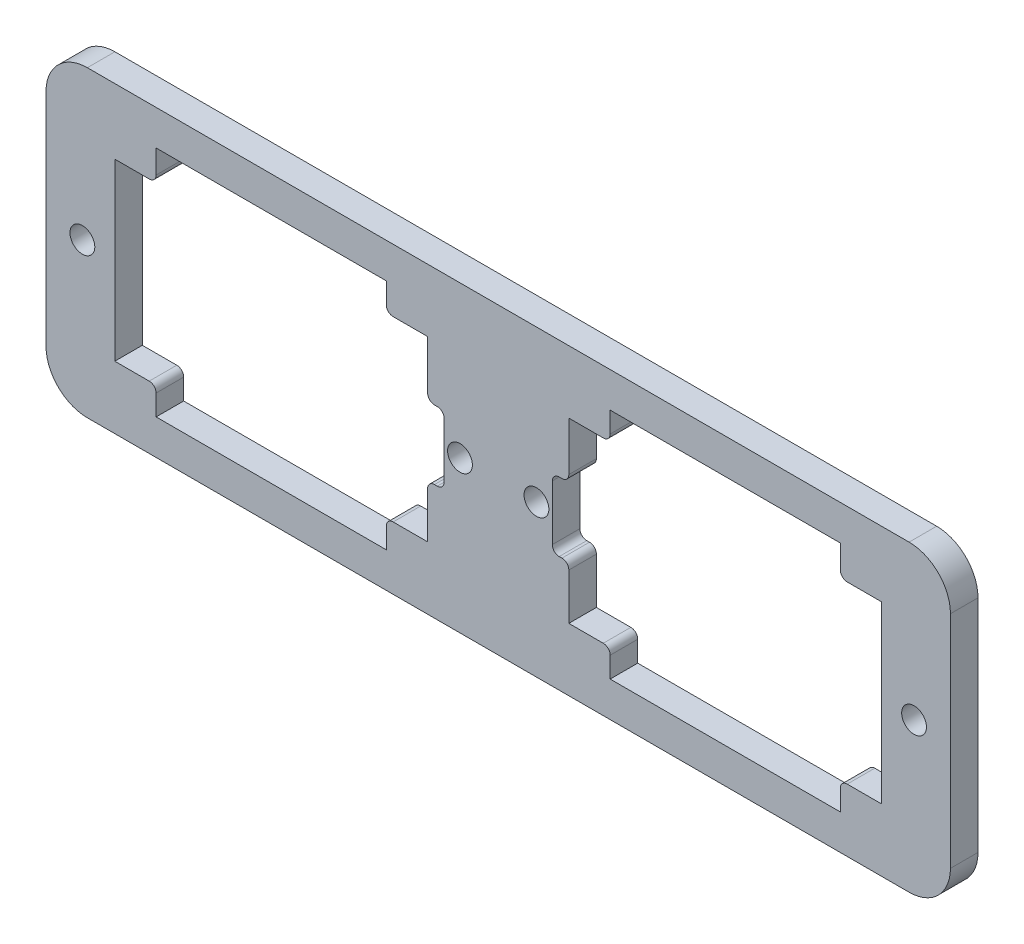
SolidWorks part; units mm, degrees
ref_plane "前视基准面" through (0, 0, 0) normal (0, 0, 1) x (1, 0, 0)
ref_plane "上视基准面" through (0, 0, 0) normal (0, 1, 0) x (1, 0, 0)
ref_plane "右视基准面" through (0, 0, 0) normal (1, 0, 0) x (0, 0, -1)
sketch "草图1" plane through (0, 0, 0) normal (0, 0, 1) x (1, 0, 0)
  line L0 (-29.8125, 11) -> (29.8125, 11)
  line L1 (32.8125, 8) -> (32.8125, -8)
  line L2 (29.8125, -11) -> (-29.8125, -11)
  line L3 (4.623, 2.4) -> (4.423, 2.4)
  line L4 (5.123, 6.45) -> (5.123, 2.9)
  line L5 (7.623, 6.45) -> (5.123, 6.45)
  line L6 (8.123, 8.45) -> (8.123, 6.95)
  line L7 (24.823, 8.45) -> (8.123, 8.45)
  line L8 (24.823, 6.75) -> (24.823, 8.45)
  line L9 (27.823, 6.25) -> (25.323, 6.25)
  line L10 (27.823, -6.45) -> (27.823, 6.25)
  line L11 (25.323, -6.45) -> (27.823, -6.45)
  line L12 (24.823, -8.45) -> (24.823, -6.95)
  line L13 (8.123, -8.45) -> (24.823, -8.45)
  line L14 (8.123, -6.95) -> (8.123, -8.45)
  line L15 (5.123, -6.45) -> (7.623, -6.45)
  line L16 (5.123, -3.1) -> (5.123, -6.45)
  line L17 (4.423, -2.6) -> (4.623, -2.6)
  line L18 (3.923, 1.9) -> (3.923, -2.1)
  line L19 (0, 11) -> (0, -11) construction
  line L20 (-32.8125, 8) -> (-32.8125, -8)
  line L21 (-3.923, 1.9) -> (-3.923, -2.1)
  line L22 (-4.423, -2.6) -> (-4.623, -2.6)
  line L23 (-5.123, -3.1) -> (-5.123, -6.45)
  line L24 (-5.123, -6.45) -> (-7.623, -6.45)
  line L25 (-8.123, -6.95) -> (-8.123, -8.45)
  line L26 (-8.123, -8.45) -> (-24.823, -8.45)
  line L27 (-24.823, -8.45) -> (-24.823, -6.95)
  line L28 (-25.323, -6.45) -> (-27.823, -6.45)
  line L29 (-27.823, -6.45) -> (-27.823, 6.25)
  line L30 (-27.823, 6.25) -> (-25.323, 6.25)
  line L31 (-24.823, 6.75) -> (-24.823, 8.45)
  line L32 (-24.823, 8.45) -> (-8.123, 8.45)
  line L33 (-8.123, 8.45) -> (-8.123, 6.95)
  line L34 (-7.623, 6.45) -> (-5.123, 6.45)
  line L35 (-5.123, 6.45) -> (-5.123, 2.9)
  line L36 (-4.623, 2.4) -> (-4.423, 2.4)
  line L37 (-30.173, 0) -> (30.173, 0) construction
  circle A0 centre (2.773, 0) radius 0.9
  circle A1 centre (30.173, 0) radius 0.9
  arc A2 (4.423, 2.4) -> (3.923, 1.9) centre (4.423, 1.9) ccw
  arc A3 (4.623, 2.4) -> (5.123, 2.9) centre (4.623, 2.9) ccw
  arc A4 (7.623, 6.45) -> (8.123, 6.95) centre (7.623, 6.95) ccw
  arc A5 (24.823, 6.75) -> (25.323, 6.25) centre (25.323, 6.75) ccw
  arc A6 (25.323, -6.45) -> (24.823, -6.95) centre (25.323, -6.95) ccw
  arc A7 (8.123, -6.95) -> (7.623, -6.45) centre (7.623, -6.95) ccw
  arc A8 (5.123, -3.1) -> (4.623, -2.6) centre (4.623, -3.1) ccw
  arc A9 (3.923, -2.1) -> (4.423, -2.6) centre (4.423, -2.1) ccw
  arc A10 (-3.923, -2.1) -> (-4.423, -2.6) centre (-4.423, -2.1) cw
  arc A11 (-5.123, -3.1) -> (-4.623, -2.6) centre (-4.623, -3.1) cw
  arc A12 (-8.123, -6.95) -> (-7.623, -6.45) centre (-7.623, -6.95) cw
  arc A13 (-25.323, -6.45) -> (-24.823, -6.95) centre (-25.323, -6.95) cw
  arc A14 (-24.823, 6.75) -> (-25.323, 6.25) centre (-25.323, 6.75) cw
  arc A15 (-7.623, 6.45) -> (-8.123, 6.95) centre (-7.623, 6.95) cw
  arc A16 (-4.623, 2.4) -> (-5.123, 2.9) centre (-4.623, 2.9) cw
  arc A17 (-4.423, 2.4) -> (-3.923, 1.9) centre (-4.423, 1.9) cw
  circle A18 centre (-30.173, 0) radius 0.9
  circle A19 centre (-2.773, 0) radius 0.9
  arc A20 (32.8125, -8) -> (29.8125, -11) centre (29.8125, -8) cw
  arc A21 (-32.8125, -8) -> (-29.8125, -11) centre (-29.8125, -8) ccw
  arc A22 (29.8125, 11) -> (32.8125, 8) centre (29.8125, 8) cw
  arc A23 (-32.8125, 8) -> (-29.8125, 11) centre (-29.8125, 8) cw
  point P81 (32.8125, -11)
  point P84 (-32.8125, -11)
  point P87 (32.8125, 11)
  point P90 (-32.8125, 11)
  dimension "D2" = 3
  dimension "D1" = 22
  dimension "D3" = 16.9
extrude "凸台-拉伸1" add sketch "草图1" along normal blind 2
